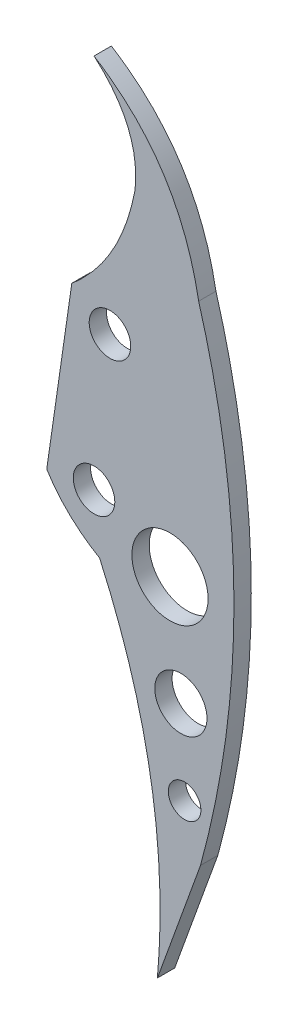
SolidWorks part; units mm, degrees
ref_plane "Plan de face" through (0, 0, 0) normal (0, 0, 1) x (1, 0, 0)
ref_plane "Plan de dessus" through (0, 0, 0) normal (0, 1, 0) x (1, 0, 0)
ref_plane "Plan de droite" through (0, 0, 0) normal (1, 0, 0) x (0, 0, -1)
sketch "Esquisse1" plane through (0, 0, 0) normal (0, 0, 1) x (1, 0, 0)
  line L0 (0, 0) -> (10.3731, 0) construction
  line L1 (10.3731, 0) -> (10.3731, 10.6518) construction
  line L2 (4.97, 4.417) -> (5.4304, 8.5395) construction
  line L3 (4.3278, 9.2682) -> (3.6031, 4.2531)
  line L7 (6.8013, -6.8829) -> (8.0475, -3.4415)
  circle A0 centre (7.1647, 3.3395) radius 1.101
  circle A1 centre (5.4304, 8.5395) radius 0.6
  circle A5 centre (7.4795, 0.328) radius 0.7537
  circle A6 centre (7.5867, -2.0534) radius 0.4707
  circle A7 centre (4.97, 4.417) radius 0.6
  spline S0 degree 2 poles (7.9933, 10.6518) (10.0065, 3.735) (8.0475, -3.4415) knots 0 0 0 1 1 1
  spline S1 degree 2 poles (5.1309, 2.7931) (7.2466, -1.8764) (6.8013, -6.8829) knots 0 0 0 1 1 1
  spline S2 degree 3 poles (3.6031, 4.2531) (3.9702, 3.6608) (4.4795, 3.1741) (5.1309, 2.7931) knots 0.419082 0.419082 0.419082 0.419082 1 1 1 1
  spline S3 degree 2 poles (7.9933, 10.6518) (7.4375, 13.7423) (4.97, 15.2768) knots 0 0 0 1 1 1
  spline S4 degree 2 poles (4.97, 15.2768) (6.3369, 14.0938) (6.1511, 12.494) knots 0 0 0 1 1 1
  spline S5 degree 3 poles (6.1511, 12.494) (5.8934, 11.1522) (5.2856, 10.077) (4.3278, 9.2682) knots 0 0 0 0 0.717085 0.717085 0.717085 0.717085
extrude "Boss.-Extru.1" add sketch "Esquisse1" along normal blind 0.5
